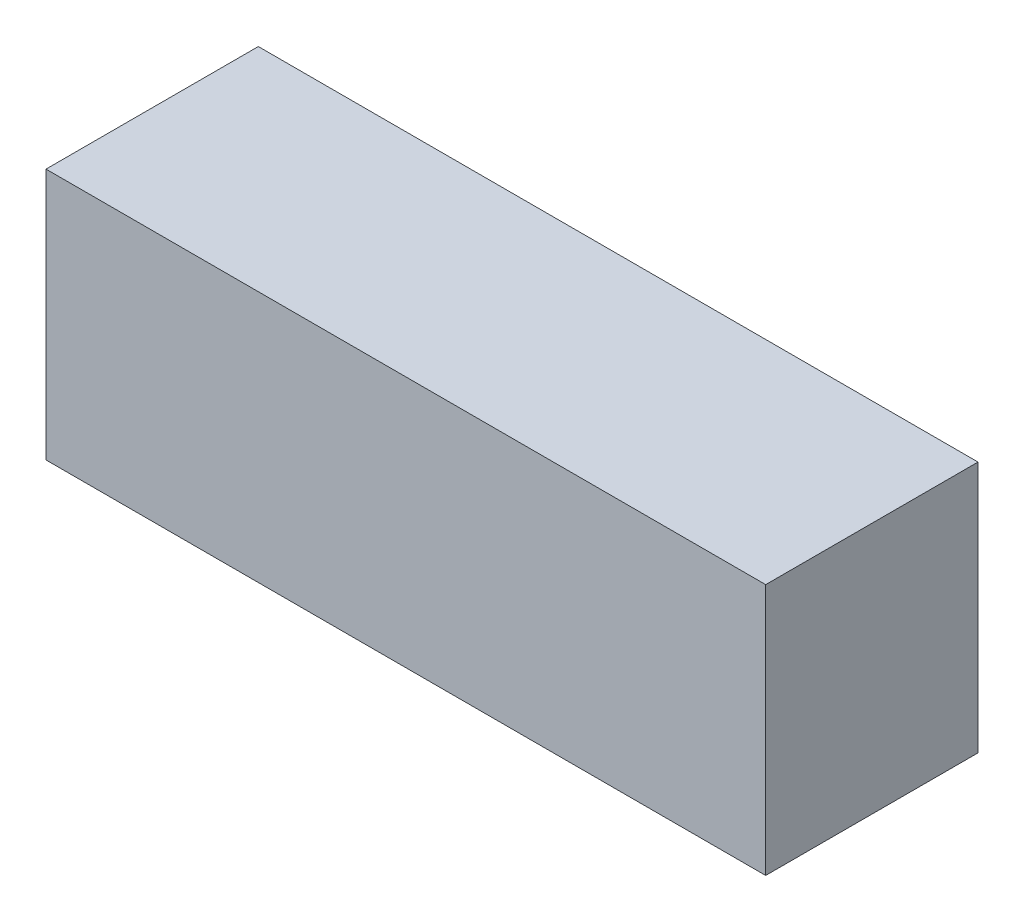
SolidWorks part; units mm, degrees
ref_plane "Front Plane" through (0, 0, 0) normal (0, 0, 1) x (1, 0, 0)
ref_plane "Top Plane" through (0, 0, 0) normal (0, 1, 0) x (1, 0, 0)
ref_plane "Right Plane" through (0, 0, 0) normal (1, 0, 0) x (0, 0, -1)
sketch "Sketch1" plane through (0, 0, 0) normal (0, 0, 1) x (1, 0, 0)
  line L0 (-60.6361, 70) -> (-60.6361, 0)
  line L1 (-60.6361, 0) -> (139.3639, 0)
  line L2 (-60.6361, 70) -> (139.3639, 70)
  line L4 (139.3639, 70) -> (139.3639, 0)
  point P2 (59.3639, 0)
  point P3 (0, 0)
  point P5 (-60.6361, 0)
  point P7 (-61.1207, 0)
  point P9 (59.8055, 0)
  dimension "D1" = 200
  dimension "D2" = 70
extrude "Boss-Extrude1" add sketch "Sketch1" along normal blind 59
sketch "Sketch5" plane through (0, 0, 0) normal (0, -1, 0) x (-1, 0, 0)
  line L1 (55.6361, -41.815) -> (20.6361, -41.815)
  line L2 (55.6361, -41.815) -> (55.6361, -17.185)
  line L3 (55.6361, -17.185) -> (20.6361, -17.185)
  line L4 (20.6361, -41.815) -> (20.6361, -17.185)
  line L10 (-39.3639, -59) -> (-39.3639, 0) construction
  line L11 (60.6361, -59) -> (-139.3639, -59) construction
  line L12 (60.6361, 0) -> (-139.3639, 0) construction
  line L13 (-139.3639, -29.5) -> (60.6361, -29.5) construction
  line L14 (-139.3639, -59) -> (-139.3639, 0) construction
  line L15 (60.6361, -59) -> (60.6361, 0) construction
  line L16 (-134.3639, -17.185) -> (-99.3639, -17.185)
  line L17 (-99.3639, -41.815) -> (-99.3639, -17.185)
  line L18 (-134.3639, -41.815) -> (-99.3639, -41.815)
  line L19 (-134.3639, -41.815) -> (-134.3639, -17.185)
  point P16 (55.6361, -29.5)
  dimension "D1" = 35
  dimension "D2" = 24.63
  dimension "D3" = 5
extrude "Cut-Extrude3" cut sketch "Sketch5" against normal blind 20
